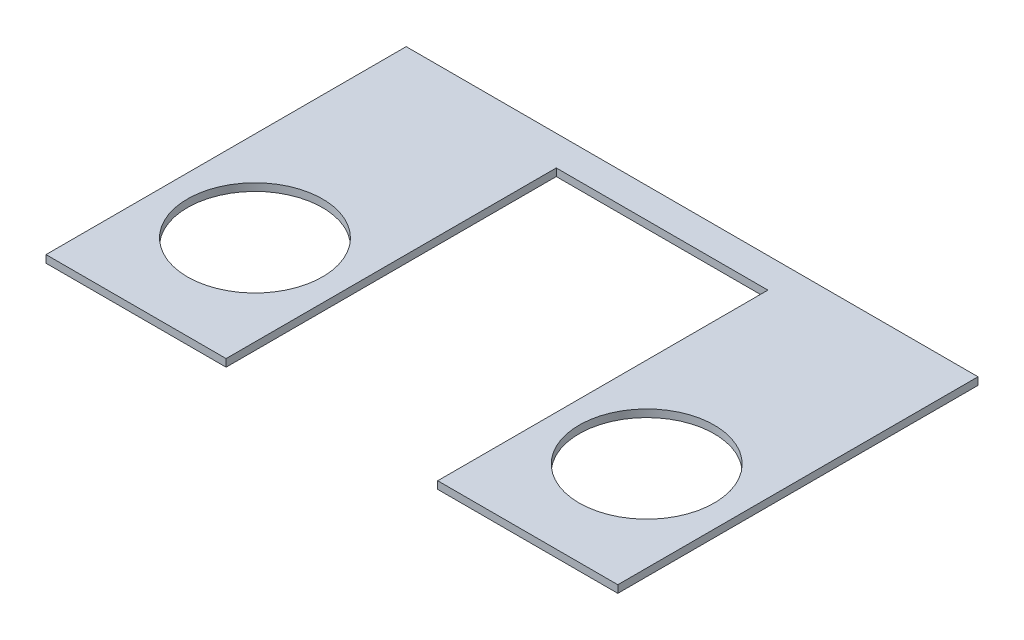
SolidWorks part; units mm, degrees
material "PVC Rigid"
ref_plane "Front Plane" through (0, 0, 0) normal (0, 0, 1) x (1, 0, 0)
ref_plane "Top Plane" through (0, 0, 0) normal (0, 1, 0) x (1, 0, 0)
ref_plane "Right Plane" through (0, 0, 0) normal (1, 0, 0) x (0, 0, -1)
sketch "Sketch1" plane through (0, 0, 0) normal (0, 1, 0) x (1, 0, 0)
  line L1 (-200, 120) -> (181, 120)
  line L2 (-200, 120) -> (-200, -120)
  line L3 (-200, -120) -> (181, -120)
  line L4 (181, 120) -> (181, -120)
  dimension "D1" = 381
  dimension "D2" = 240
  dimension "D3" = 120
  dimension "D4" = 200
extrude "Boss-Extrude1" add sketch "Sketch1" along normal blind 5
sketch "Sketch2" plane through (0, 5, 0) normal (0, 1, 0) x (1, 0, 0)
  line L1 (181, -120) -> (181, 120) construction
  line L3 (181, 120) -> (-200, 120) construction
  circle A0 centre (-140, -40.75) radius 45
  circle A1 centre (121, -40.75) radius 45
  dimension "D2" = 90
  dimension "D3" = 90
  dimension "D5" = 160.75
  dimension "D6" = 60
  dimension "D4" = 160.75
  dimension "D1" = 261
extrude "Cut-Extrude1" cut sketch "Sketch2" against normal blind 5
sketch "Sketch5" plane through (0, 5, 0) normal (0, 1, 0) x (1, 0, 0)
  line L0 (-200, -120) -> (181, -120) construction
  line L1 (61, -120) -> (-80, -120)
  line L2 (61, -120) -> (61, 100)
  line L3 (61, 100) -> (-80, 100)
  line L4 (-80, -120) -> (-80, 100)
  line L5 (181, -120) -> (181, 120) construction
  line L6 (181, 120) -> (-200, 120) construction
  dimension "D1" = 141
  dimension "D2" = 120
  dimension "D3" = 20
extrude "Cut-Extrude3" cut sketch "Sketch5" against normal blind 5
